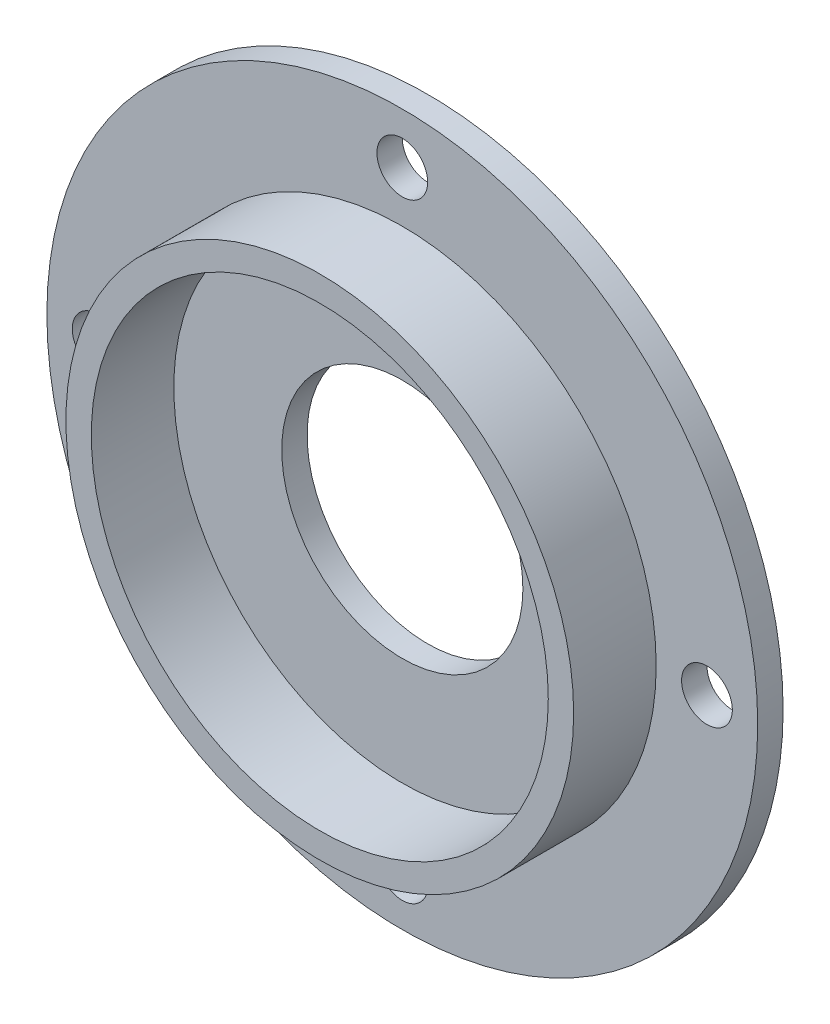
SolidWorks part; units mm, degrees
ref_plane "前视" through (0, 0, 0) normal (0, 0, 1) x (1, 0, 0)
ref_plane "上视" through (0, 0, 0) normal (0, 1, 0) x (1, 0, 0)
ref_plane "右视" through (0, 0, 0) normal (1, 0, 0) x (0, 0, -1)
sketch "草图1" plane through (0, 0, 0) normal (0, 0, 1) x (1, 0, 0)
  line L0 (0, 155.7418) -> (0, -151.0312) construction
  line L1 (155.2911, 0) -> (-154.426, 0) construction
  circle A0 centre (0, 0) radius 140
  circle A1 centre (0, 0) radius 47.5
  circle A2 centre (0, 0) radius 120 construction
  circle A3 centre (0, 120) radius 10
  circle A4 centre (120, 0) radius 10
  circle A5 centre (0, -120) radius 10
  circle A6 centre (-120, 0) radius 10
  dimension "D1" = 95
  dimension "D2" = 280
  dimension "D3" = 240
  dimension "D4" = 20
  dimension "D5" = 20
  dimension "D6" = 20
  dimension "D7" = 20
extrude "拉伸1" add sketch "草图1" along normal blind 10
sketch "草图2" plane through (0, 0, 10) normal (0, 0, 1) x (1, 0, 0)
  circle A0 centre (0, 0) radius 100
  circle A1 centre (0, 0) radius 90
  dimension "D1" = 180
  dimension "D2" = 200
extrude "拉伸2" add sketch "草图2" along normal blind 32.5
